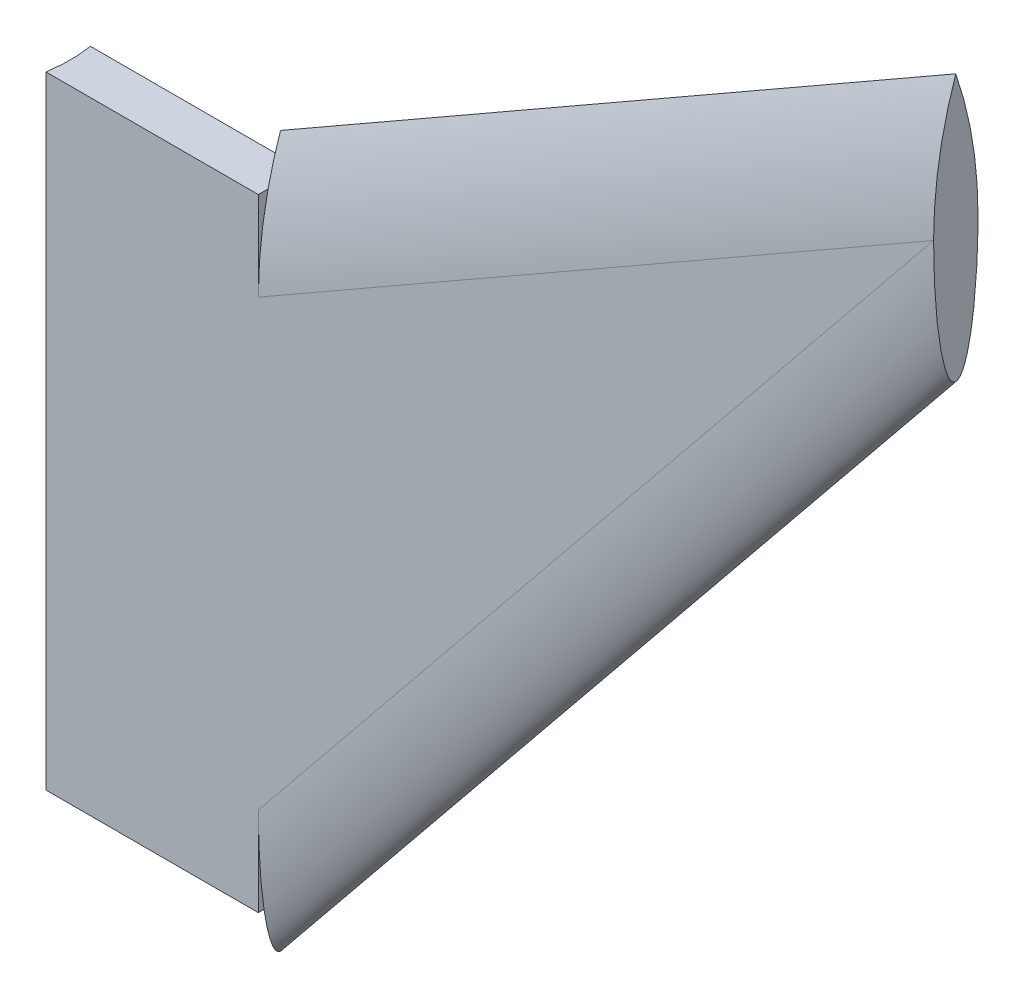
SolidWorks part; units mm, degrees
other "Markup1"
sketch "Sketch2" plane through (0, -5, 5) normal (-0.9994, -0.0223, 0.0275) x (0.021, 0.2509, 0.9678)
ref_plane "Front Plane" through (0, 0, 0) normal (0, 0, 1) x (1, 0, 0)
ref_plane "Top Plane" through (0, 0, 0) normal (0, 1, 0) x (1, 0, 0)
ref_plane "Right Plane" through (0, 0, 0) normal (1, 0, 0) x (0, 0, -1)
sketch "Sketch1" plane through (0, 0, 0) normal (0, 0, 1) x (1, 0, 0)
  line L0 (0, 0) -> (0, 70)
  line L1 (0, 70) -> (25, 70)
  line L5 (101, 88.518) -> (25, -5)
  line L6 (25, -5) -> (25, 0)
  line L7 (25, 0) -> (0, 0)
  line L8 (25, 70) -> (25, 75)
  line L9 (25, 75) -> (101, 118.518)
  line L10 (101, 118.518) -> (101, 88.518)
  line L11 (25, 75) -> (25, -5) construction
  line L12 (25, -5) -> (132.0264, -5) construction
  point P3 (25, 35)
  point P10 (0, 35)
  dimension "D1" = 80
  dimension "D2" = 30
  dimension "D3" = 76
  dimension "D4" = 25
  dimension "D5" = 70
  dimension "D6" = 50.9
extrude "Boss-Extrude1" add sketch "Sketch1" along normal blind 5
sketch "Sketch4" plane through (101, 0, 0) normal (1, 0, 0) x (0, 0, -1)
  line L0 (-2.5, 118.518) -> (-2.5, 88.518) construction
  line L1 (-5, 88.518) -> (0, 88.518) construction
  line L2 (-5, 88.518) -> (-5, 118.518) construction
  line L3 (0, 88.518) -> (0, 118.518) construction
  line L7 (0, 103.518) -> (-5, 103.518)
  line L8 (-5, 118.518) -> (0, 118.518) construction
  line L9 (0, 88.518) -> (0, 103.518)
  line L10 (-5, 88.518) -> (0, 88.518)
  line L11 (-5, 103.518) -> (-5, 88.518)
  arc A0 (0, 103.518) -> (-2.5, 118.518) centre (-46.25, 103.518) ccw
  arc A1 (-5, 103.518) -> (-2.5, 118.518) centre (41.25, 103.518) cw
  ellipse E0 centre (-2.5, 103.518) end of major axis (-2.5, 88.518) minor radius 2.5 (-5, 103.518) -> (0, 103.518) ccw
  line M3 (0, 88.518) -> (0, 118.518)
  line M5 (-5, 118.518) -> (-5, 88.518)
  line M6 (-5, 88.518) -> (0, 88.518)
  dimension "D1" = 15
extrude "Cut-Extrude2" cut sketch "Sketch4" along direction (0.6307, 0.776, 0) on the side against the normal up to surface (76 mm away) contours E0 L10 M3 | E0 M5 M6
sketch "Sketch5" plane through (101, 0, 0) normal (1, 0, 0) x (0, 0, -1)
  line L0 (-5, 118.518) -> (0, 118.518) construction
  line L1 (0, 103.518) -> (0, 118.518)
  line L2 (-2.5, 118.518) -> (-2.5, 88.518) construction
  line L3 (0, 103.518) -> (-5, 103.518)
  line L4 (0, 88.518) -> (0, 103.518)
  line L5 (-5, 88.518) -> (0, 88.518)
  line L6 (-5, 103.518) -> (-5, 88.518)
  line L7 (0, 118.518) -> (-5, 118.518)
  line L8 (-5, 118.518) -> (-5, 103.518)
  arc A1 (0, 103.518) -> (-2.5, 118.518) centre (-46.25, 103.518) ccw
  arc A2 (-5, 103.518) -> (-2.5, 118.518) centre (41.25, 103.518) cw
  ellipse E1 centre (-2.5, 103.518) end of major axis (-2.5, 88.518) minor radius 2.5 (-5, 103.518) -> (0, 103.518) ccw
  point P13 (-2.5, 118.518)
  dimension "D1" = 15
extrude "Cut-Extrude3" cut sketch "Sketch5" along direction (-0.8678, -0.4969, 0) on the side against the normal up to surface (76 mm away)
sketch "Sketch6" plane through (0, 70, 0) normal (0, 1, 0) x (1, 0, 0)
  line L1 (25, -2.5) -> (-26.1039, -2.5) construction
  line L3 (0, -5) -> (0, 0) construction
  circle A2 centre (-14.6, -2.5) radius 39.6
  circle A3 centre (-14.6, -2.5) radius 15.9
  point P9 (0, -2.5)
  dimension "D1" = 79.2
  dimension "D2" = 31.8
extrude "Cut-Extrude7" cut sketch "Sketch6" against normal through all contours A3
